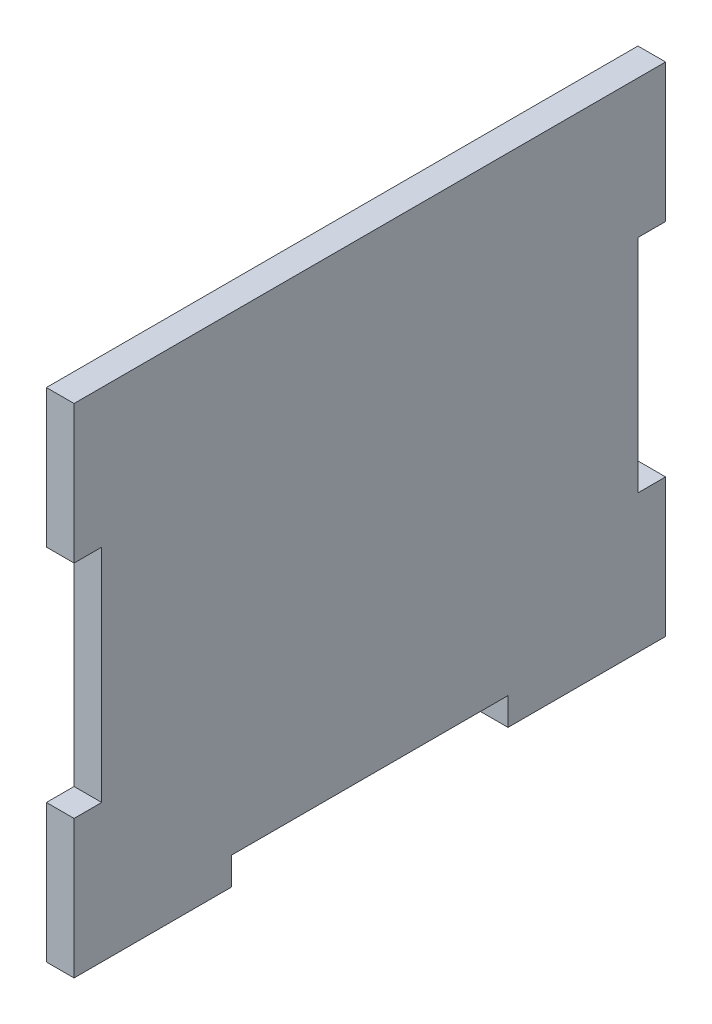
SolidWorks part; units mm, degrees
ref_plane "Front Plane" through (0, 0, 0) normal (0, 0, 1) x (1, 0, 0)
ref_plane "Top Plane" through (0, 0, 0) normal (0, 1, 0) x (1, 0, 0)
ref_plane "Right Plane" through (0, 0, 0) normal (1, 0, 0) x (0, 0, -1)
sketch "Sketch1" plane through (0, 0, 0) normal (1, 0, 0) x (0, 0, -1)
  line L1 (0, 0) -> (107, 0)
  line L2 (0, 0) -> (0, 90)
  line L3 (0, 90) -> (107, 90)
  line L4 (107, 0) -> (107, 90)
  dimension "D1" = 107
  dimension "D2" = 90
extrude "Boss-Extrude1" add sketch "Sketch1" along normal blind 5
sketch "Sketch5" plane through (0, 0, 0) normal (-1, 0, 0) x (0, 0, 1)
  line L0 (-107, 0) -> (-107, 90) construction
  line L1 (-107, 65) -> (-102, 65)
  line L2 (-107, 65) -> (-107, 25)
  line L3 (-107, 25) -> (-102, 25)
  line L4 (-102, 65) -> (-102, 25)
  line L5 (0, 0) -> (-107, 0) construction
  line L6 (0, 90) -> (0, 0) construction
  line L7 (0, 65) -> (-5, 65)
  line L8 (0, 65) -> (0, 25)
  line L9 (0, 25) -> (-5, 25)
  line L10 (-5, 65) -> (-5, 25)
  line L12 (-78.5, 0) -> (-28.5, 0)
  line L13 (-78.5, 0) -> (-78.5, 5)
  line L14 (-78.5, 5) -> (-28.5, 5)
  line L15 (-28.5, 0) -> (-28.5, 5)
  dimension "D1" = 5
  dimension "D2" = 40
  dimension "D3" = 25
  dimension "D4" = 5
  dimension "D5" = 50
  dimension "D6" = 5
  dimension "D7" = 28.5
  dimension "D8" = 40
  dimension "D9" = 25
extrude "Cut-Extrude2" cut sketch "Sketch5" against normal through all
sketch "Sketch6" plane through (0, 0, 0) normal (-1, 0, 0) x (0, 0, 1)
  line L1 (-104.5, 87.5) -> (-2.5, 87.5)
  line L2 (-104.5, 87.5) -> (-104.5, 84.5)
  line L3 (-104.5, 84.5) -> (-2.5, 84.5)
  line L4 (-2.5, 87.5) -> (-2.5, 84.5)
  line L5 (-107, 90) -> (0, 90) construction
  line L6 (0, 90) -> (0, 65) construction
  dimension "D1" = 102
  dimension "D2" = 3
  dimension "D3" = 2.5
  dimension "D4" = 2.5
extrude "Cut-Extrude3" cut sketch "Sketch6" against normal blind 2.5
equation "\"D7@Sketch5\"=(107-50)/2mm"
